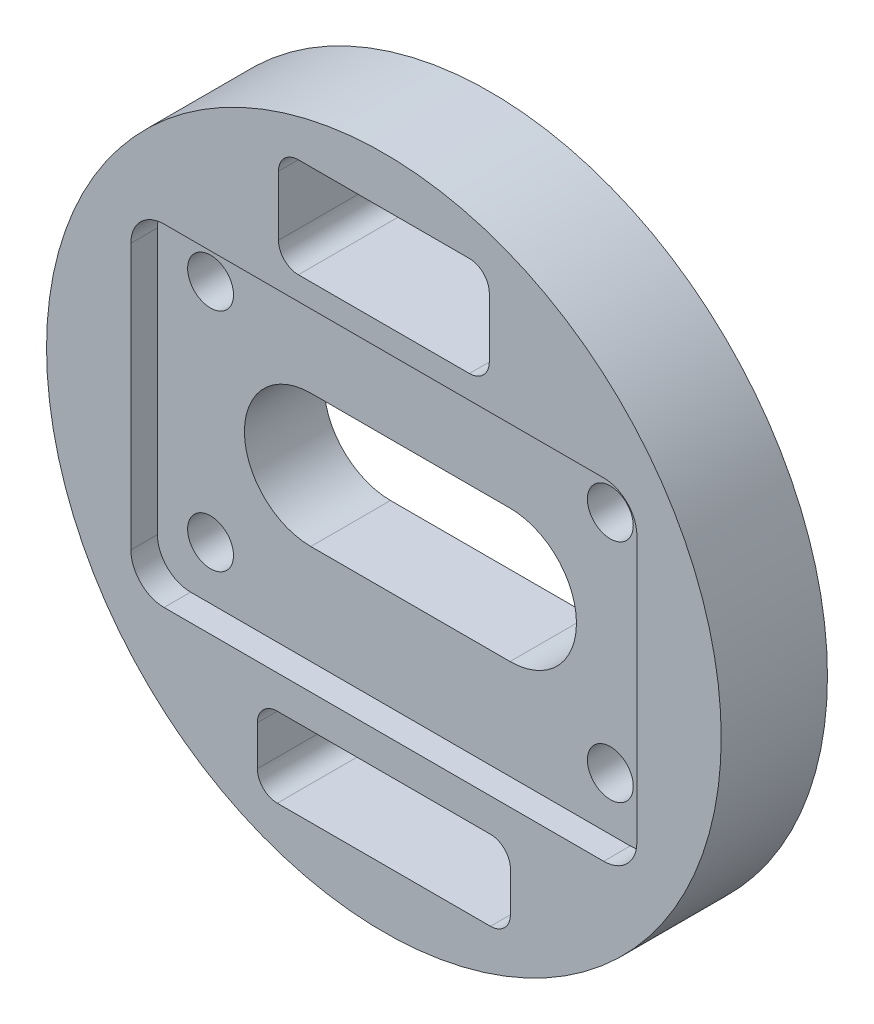
SolidWorks part; units mm, degrees
ref_plane "Front Plane" through (0, 0, 0) normal (0, 0, 1) x (1, 0, 0)
ref_plane "Top Plane" through (0, 0, 0) normal (0, 1, 0) x (1, 0, 0)
ref_plane "Right Plane" through (0, 0, 0) normal (1, 0, 0) x (0, 0, -1)
sketch "Sketch1" plane through (0, 0, 0) normal (0, 0, 1) x (1, 0, 0)
  circle A0 centre (0, 0) radius 25.4
  dimension "D1" = 50.8
extrude "Boss-Extrude1" add sketch "Sketch1" against normal blind 8
sketch "Sketch2" plane through (0, 0, 0) normal (0, 0, 1) x (1, 0, 0)
  line L1 (-16.55, 12.5) -> (16.55, 12.5)
  line L2 (-19.05, 10) -> (-19.05, -10)
  line L3 (-16.55, -12.5) -> (16.55, -12.5)
  line L4 (19.05, 10) -> (19.05, -10)
  line L5 (-19.05, 12.5) -> (19.05, -12.5) construction
  line L6 (-19.05, -12.5) -> (19.05, 12.5) construction
  arc A0 (16.55, -12.5) -> (19.05, -10) centre (16.55, -10) ccw
  arc A1 (-19.05, -10) -> (-16.55, -12.5) centre (-16.55, -10) ccw
  arc A2 (-16.55, 12.5) -> (-19.05, 10) centre (-16.55, 10) ccw
  arc A3 (16.55, 12.5) -> (19.05, 10) centre (16.55, 10) cw
  point P0 (0, 0)
  dimension "D3" = 2.5
  dimension "D1" = 38.1
  dimension "D2" = 25
extrude "Cut-Extrude1" cut sketch "Sketch2" against normal blind 2
sketch "Sketch3" plane through (0, 0, -2) normal (0, 0, 1) x (1, 0, 0)
  line L0 (-7.5, 0) -> (7.5, 0) construction
  line L1 (-7.5, 5) -> (7.5, 5)
  line L2 (-7.5, -5) -> (7.5, -5)
  arc A0 (-7.5, 5) -> (-7.5, -5) centre (-7.5, 0) ccw
  arc A1 (7.5, -5) -> (7.5, 5) centre (7.5, 0) ccw
  point P3 (0, 0)
  dimension "D2" = 5
  dimension "D1" = 15
extrude "Cut-Extrude2" cut sketch "Sketch3" against normal through all
hole_wizard "#8-32 Tapped Hole1" positions "Sketch4" profile "Sketch5" tap size "#8-32" standard "ANSI Inch" end condition up to next
sketch "Sketch4" plane through (0, 0, -2) normal (0, 0, 1) x (1, 0, 0)
  line L0 (19.05, -10) -> (19.05, 10) construction
  line L1 (16.55, 12.5) -> (-16.55, 12.5) construction
  line L2 (0, 0) -> (0, 25.4) construction
  line L3 (0, 0) -> (25.4, 0) construction
  circle A0 centre (0, 0) radius 25.4 construction
  point P0 (15.05, 8.5)
  point P20 (-15.05, 8.5)
  point P21 (-15.05, -8.5)
  point P22 (15.05, -8.5)
  dimension "D1" = 4
  dimension "D2" = 4
cosmetic thread "Hole Thread1"
cosmetic thread "Hole Thread2"
cosmetic thread "Hole Thread3"
cosmetic thread "Hole Thread4"
sketch "Sketch5" plane through (15.05, 8.5, -2) normal (1, 0, 0) x (0, -1, 0)
  line L0 (0, 0) -> (0, 6)
  line L1 (0, 6) -> (1.7272, 6)
  line L2 (1.7272, 6) -> (1.7272, 0)
  line L5 (1.7272, 0) -> (0, 0)
  line L11 (0, -6.35) -> (0, 107.95) construction
  dimension "Thru Tap Drill Dia." = 3.4544
  dimension "Thru Tap Drill Depth" = 6
sketch "Sketch6" plane through (0, 0, 0) normal (0, 0, 1) x (1, 0, 0)
  line L0 (0, 0) -> (0, 25.4) construction
  line L2 (6.4375, 21.75) -> (-6.4375, 21.75)
  line L3 (7.9375, 20.25) -> (7.9375, 15.75)
  line L4 (6.4375, 14.25) -> (-6.4375, 14.25)
  line L5 (-7.9375, 20.25) -> (-7.9375, 15.75)
  line L6 (7.9375, 21.75) -> (-7.9375, 14.25) construction
  line L7 (7.9375, 14.25) -> (-7.9375, 21.75) construction
  circle A0 centre (0, 0) radius 25.4 construction
  arc A1 (7.9375, 15.75) -> (6.4375, 14.25) centre (6.4375, 15.75) cw
  arc A2 (-6.4375, 14.25) -> (-7.9375, 15.75) centre (-6.4375, 15.75) cw
  arc A3 (-6.4375, 21.75) -> (-7.9375, 20.25) centre (-6.4375, 20.25) ccw
  arc A4 (6.4375, 21.75) -> (7.9375, 20.25) centre (6.4375, 20.25) cw
  point P6 (0, 18)
  dimension "D4" = 1.5
  dimension "D1" = 18
  dimension "D2" = 15.875
  dimension "D3" = 7.5
extrude "Cut-Extrude3" cut sketch "Sketch6" against normal through all
sketch "Sketch7" plane through (0, 0, 0) normal (0, 0, 1) x (1, 0, 0)
  line L0 (0, 0) -> (0, -25.4) construction
  line L2 (-9.525, -21) -> (9.525, -21)
  line L3 (-9.525, -21) -> (-9.525, -15)
  line L4 (-9.525, -15) -> (9.525, -15)
  line L5 (9.525, -21) -> (9.525, -15)
  line L6 (-9.525, -21) -> (9.525, -15) construction
  line L7 (-9.525, -15) -> (9.525, -21) construction
  circle A0 centre (0, 0) radius 25.4 construction
  point P6 (0, -18)
  dimension "D1" = 6
  dimension "D2" = 19.05
  dimension "D3" = 18
extrude "Cut-Extrude4" cut sketch "Sketch7" against normal through all
fillet "Fillet1" radius 1.5 4 edges at (9.525, -21, -4) (-9.525, -21, -4) (-9.525, -15, -4) (9.525, -15, -4)
